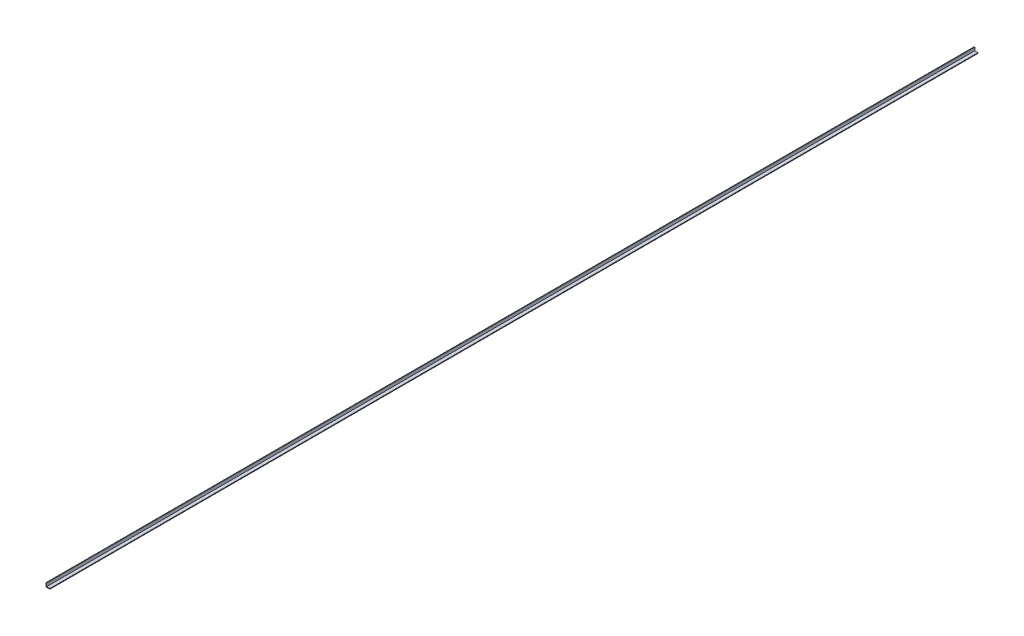
SolidWorks part; units mm, degrees
material "ASTM A36 Acero"
ref_plane "Alzado" through (0, 0, 0) normal (0, 0, 1) x (1, 0, 0)
ref_plane "Planta" through (0, 0, 0) normal (0, 1, 0) x (1, 0, 0)
ref_plane "Vista lateral" through (0, 0, 0) normal (1, 0, 0) x (0, 0, -1)
sketch "Croquis1" plane through (0, 0, 0) normal (0, 0, 1) x (1, 0, 0)
  line L0 (0, 25.4) -> (0, 0)
  line L1 (0, 0) -> (25.4, 0)
  line L2 (25.4, 0) -> (25.4, 4.76)
  line L3 (25.4, 4.76) -> (4.76, 4.76)
  line L4 (4.76, 4.76) -> (4.76, 25.4)
  line L5 (4.76, 25.4) -> (0, 25.4)
  dimension "D1" = 4.76
  dimension "D2" = 25.4
extrude "Saliente-Extruir1" add sketch "Croquis1" against normal blind 6100
